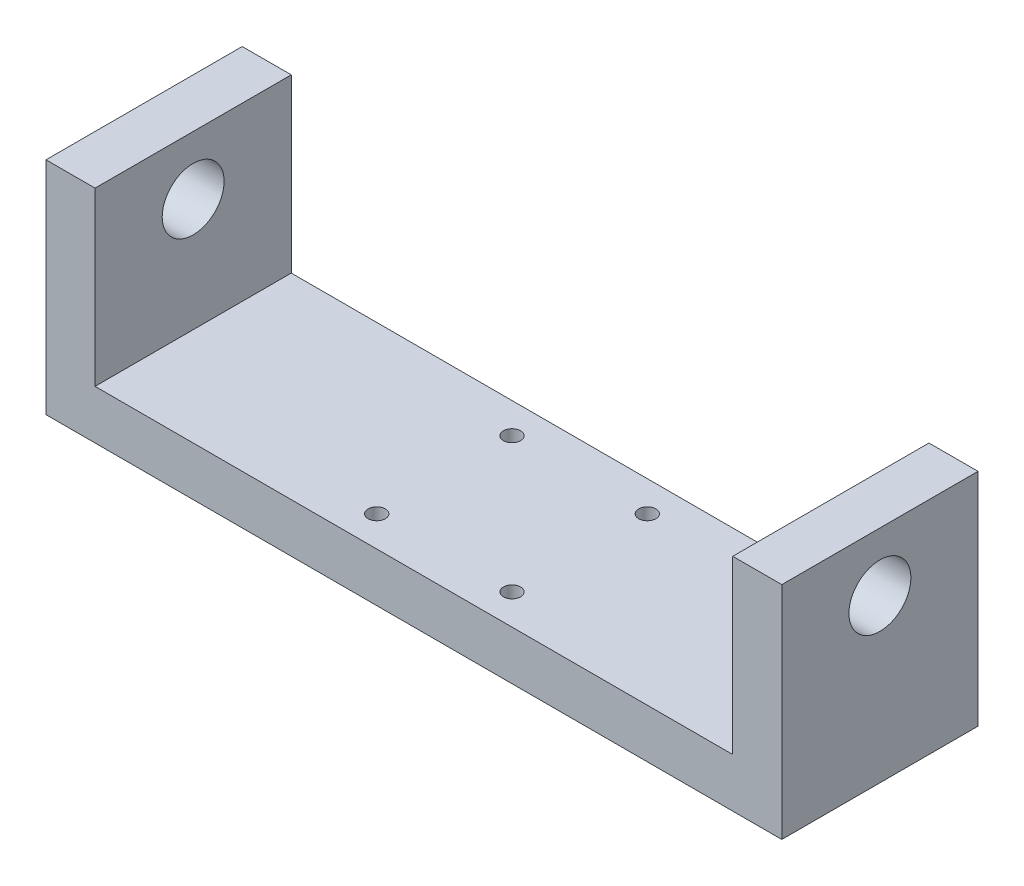
SolidWorks part; units mm, degrees
ref_plane "Plan de face" through (0, 0, 0) normal (0, 0, 1) x (1, 0, 0)
ref_plane "Plan de dessus" through (0, 0, 0) normal (0, 1, 0) x (1, 0, 0)
ref_plane "Plan de droite" through (0, 0, 0) normal (1, 0, 0) x (0, 0, -1)
sketch "Esquisse1" plane through (0, 0, 0) normal (0, 0, 1) x (1, 0, 0)
  line L0 (0, 100.7103) -> (0, -76.0246) construction
  line L1 (-65, 45) -> (-75, 45)
  line L2 (-75, 0) -> (75, 0)
  line L3 (75, 0) -> (75, 45)
  line L4 (-65, 10) -> (65, 10)
  line L5 (65, 10) -> (65, 45)
  line L6 (65, 45) -> (75, 45)
  line L7 (-65, 10) -> (-65, 45)
  line L8 (-75, 0) -> (-75, 45)
  point P13 (0, 10)
  point P14 (0, 0)
  dimension "D1" = 130
  dimension "D2" = 10
  dimension "D3" = 10
  dimension "D4" = 35
extrude "Boss.-Extru.1" add sketch "Esquisse1" along normal blind 40 contours L1 L8 L2 L3 L6 L5 L4 L7
sketch "Esquisse2" plane through (0, 10, 0) normal (0, 1, 0) x (1, 0, 0)
  line L0 (0, 0) -> (0, -40) construction
  line L1 (0, -20) -> (-65, -20) construction
  line L2 (-65, 0) -> (65, 0) construction
  line L3 (-65, -40) -> (65, -40) construction
  line L4 (-65, -40) -> (-65, 0) construction
  circle A0 centre (-13.7886, -6.2114) radius 1.75
  circle A1 centre (13.7886, -6.2114) radius 1.75
  circle A2 centre (13.7886, -33.7886) radius 1.75
  circle A3 centre (-13.7886, -33.7886) radius 1.75
  point P6 (0, 0)
  point P23 (0, -20)
  dimension "D12" = 3.5
  dimension "D3" = 19.5
  dimension "D4" = 45
extrude "Enlèv. mat.-Extru.1" cut sketch "Esquisse2" against normal through all
sketch "Esquisse5" plane through (-75, 0, 0) normal (-1, 0, 0) x (0, 0, 1)
  line L0 (20, 45) -> (20, 0) construction
  line L1 (40, 45) -> (0, 45) construction
  line L2 (40, 0) -> (0, 0) construction
  line L3 (20, 0) -> (20, 45) construction
  circle A0 centre (20, 33.0538) radius 6.3126
  dimension "D2" = 12.6252
  dimension "D1" = 11.9462
extrude "Enlèv. mat.-Extru.2" cut sketch "Esquisse5" against normal through all
equation "\"diamtreVis\"= 3.5mm"
equation "\"diametreVolant\"= 100mm"
equation "\"margeRotation\"= 15mm"
equation "\"dimaetreCercleVisMoteur\"= 19.5mm"
equation "\"D12@Esquisse2\"=\"diamtreVis\""
equation "\"D3@Esquisse2\"=\"dimaetreCercleVisMoteur\""
equation "\"largeurSupportRotation\"= 40mm"
equation "\"D1@Boss.-Extru.1\"= \"largeurSupportRotation\""
equation "\"D1@Esquisse1\"= \"diametreVolant\" + 2 * \"margeRotation\""
equation "\"epaisseurEnsembleRotation\"= 10"
equation "\"D2@Esquisse1\"=\"epaisseurEnsembleRotation\""
equation "\"D3@Esquisse1\"=\"epaisseurEnsembleRotation\""
equation "\"dimatreServo\"=12.6252"
equation "\"D2@Esquisse5\"=\"dimatreServo\""
equation "\"hauteurEnsembleRotation\"=35"
equation "\"D4@Esquisse1\"=\"hauteurEnsembleRotation\""
